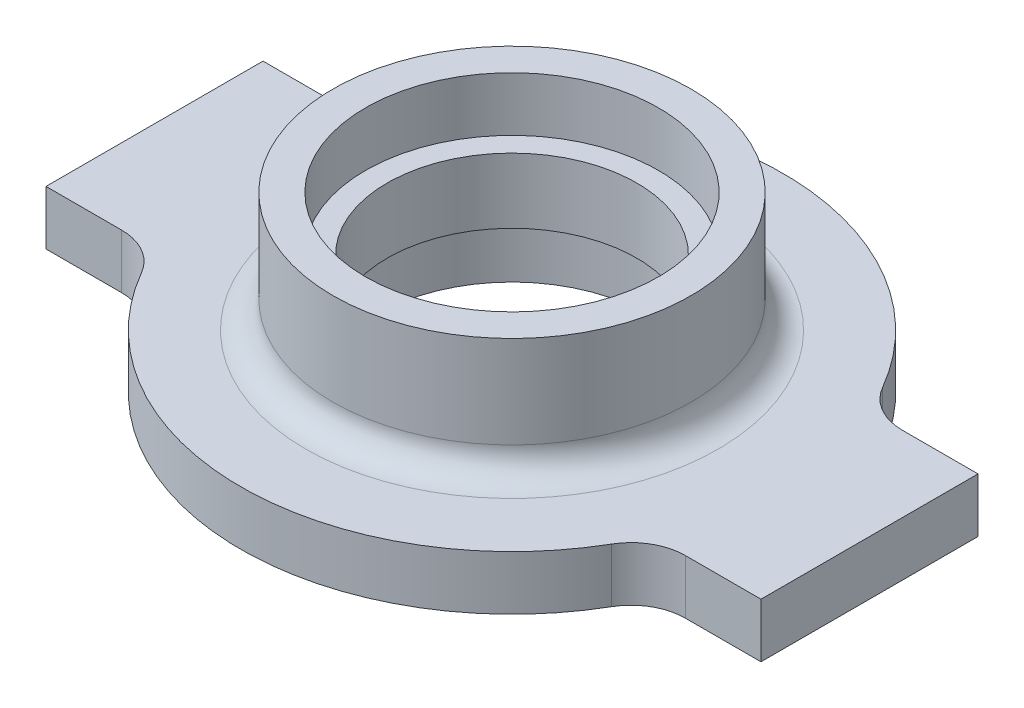
SolidWorks part; units mm, degrees
ref_plane "Front Plane" through (0, 0, 0) normal (0, 0, 1) x (1, 0, 0)
ref_plane "Top Plane" through (0, 0, 0) normal (0, 1, 0) x (1, 0, 0)
ref_plane "Right Plane" through (0, 0, 0) normal (1, 0, 0) x (0, 0, -1)
sketch "Sketch1" plane through (0, 0, 0) normal (0, 1, 0) x (1, 0, 0)
  line L0 (-22.9129, 10) -> (-32.945, 10)
  line L1 (32.945, -10) -> (22.9129, -10)
  line L2 (32.945, -10) -> (32.945, 10)
  line L3 (32.945, 10) -> (22.9129, 10)
  line L4 (-32.945, -10) -> (-32.945, 10)
  line L5 (32.945, -10) -> (-32.945, 10) construction
  line L6 (32.945, 10) -> (-32.945, -10) construction
  line L7 (-22.9129, -10) -> (-32.945, -10)
  arc A0 (-22.9129, -10) -> (22.9129, -10) centre (0, 0) ccw
  arc A1 (22.9129, 10) -> (-22.9129, 10) centre (0, 0) ccw
  circle A2 centre (0, 0) radius 12.5
  dimension "D1" = 25
  dimension "D4" = 25
  dimension "D2" = 65.89
  dimension "D3" = 20
extrude "Boss-Extrude1" add sketch "Sketch1" along normal blind 5
sketch "Sketch2" plane through (0, 5, 0) normal (0, 1, 0) x (1, 0, 0)
  circle A0 centre (0, 0) radius 16.5
  circle A1 centre (0, 0) radius 11.5
  dimension "D1" = 33
  dimension "D2" = 23
extrude "Boss-Extrude2" add sketch "Sketch2" along normal blind 6
sketch "Sketch3" plane through (0, 11, 0) normal (0, 1, 0) x (1, 0, 0)
  circle A0 centre (0, 0) radius 13.5
  circle A1 centre (0, 0) radius 16.5
  circle A2 centre (0, 0) radius 16.5 construction
  dimension "D1" = 27
extrude "Boss-Extrude3" add sketch "Sketch3" along normal blind 5
fillet "Fillet1" radius 2.5 1 edges at (0, 5, 16.5)
fillet "Fillet2" radius 5 4 edges at (-22.9129, 2.5, -10) (22.9129, 2.5, -10) (-22.9129, 2.5, 10) (22.9129, 2.5, 10)
